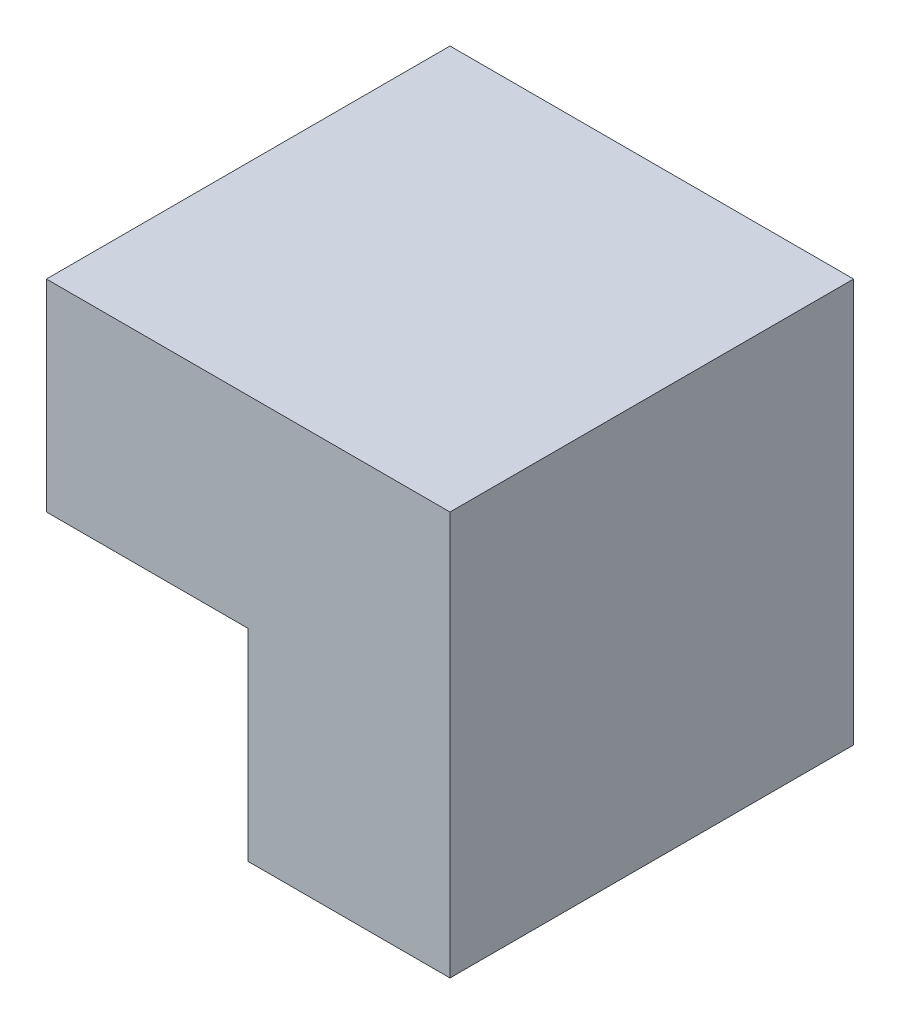
SolidWorks part; units mm, degrees
ref_plane "前视基准面" through (0, 0, 0) normal (0, 0, 1) x (1, 0, 0)
ref_plane "上视基准面" through (0, 0, 0) normal (0, 1, 0) x (1, 0, 0)
ref_plane "右视基准面" through (0, 0, 0) normal (1, 0, 0) x (0, 0, -1)
other "Configuration Table"
sketch "SelectionSeed" plane through (0, 0, 0) normal (0, 0, 1) x (1, 0, 0)
  line L1 (0, 0) -> (10, 0)
  line L2 (0, 0) -> (0, 10)
  line L3 (0, 10) -> (10, 10)
  line L4 (10, 0) -> (10, 10)
  line L6 (5, 5) -> (15, 5)
  line L7 (5, 5) -> (5, 15)
  line L8 (5, 15) -> (15, 15)
  line L9 (15, 5) -> (15, 15)
extrude "SelectionExtrude" add sketch "SelectionSeed" along normal blind 10 contours L6 L9 L8 L7 L3 L4
